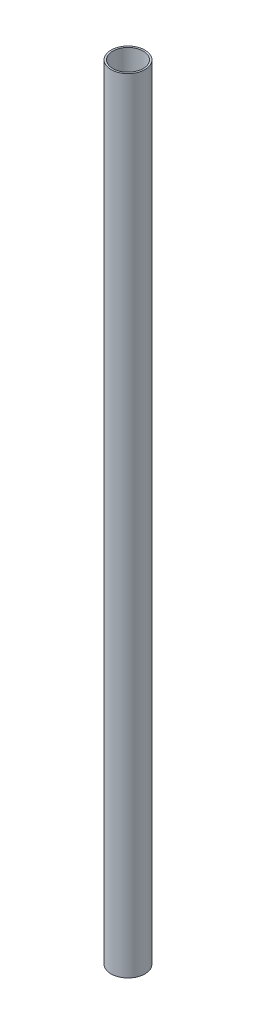
SolidWorks part; units mm, degrees
material "3003-H14"
ref_plane "Front Plane" through (0, 0, 0) normal (0, 0, 1) x (1, 0, 0)
ref_plane "Top Plane" through (0, 0, 0) normal (0, 1, 0) x (1, 0, 0)
ref_plane "Right Plane" through (0, 0, 0) normal (1, 0, 0) x (0, 0, -1)
sketch "Sketch1" plane through (0, 0, 0) normal (0, 1, 0) x (1, 0, 0)
  line L0 (0, 0) -> (3.5624, 0) construction
  line L1 (3.5624, 0) -> (3.9688, 0) construction
  circle A0 centre (0, 0) radius 3.9688
  circle A1 centre (0, 0) radius 3.5624
  dimension "D1" = 7.9375
  dimension "D2" = 0.4064
extrude "Boss-Extrude1" add sketch "Sketch1" along normal blind 183.642
